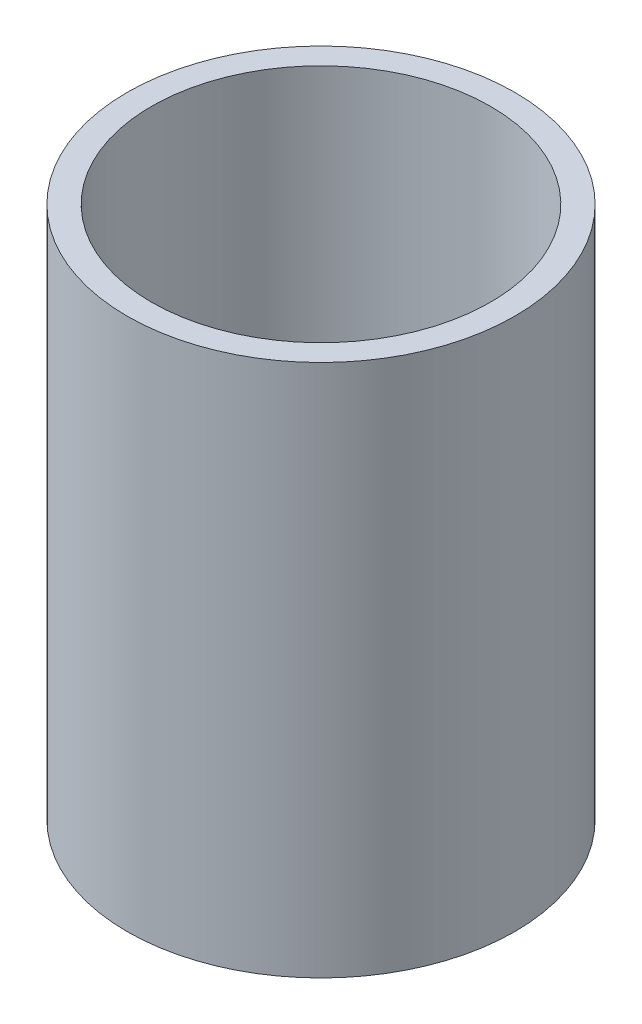
SolidWorks part; units mm, degrees
ref_plane "Front Plane" through (0, 0, 0) normal (0, 0, 1) x (1, 0, 0)
ref_plane "Top Plane" through (0, 0, 0) normal (0, 1, 0) x (1, 0, 0)
ref_plane "Right Plane" through (0, 0, 0) normal (1, 0, 0) x (0, 0, -1)
sketch "Sketch2" plane through (0, 0, 0) normal (0, 1, 0) x (1, 0, 0)
  circle A0 centre (0, 0) radius 40
  circle A1 centre (0, 0) radius 35
  dimension "D1" = 80
  dimension "D2" = 70
extrude "Boss-Extrude1" add sketch "Sketch2" along normal blind 110
